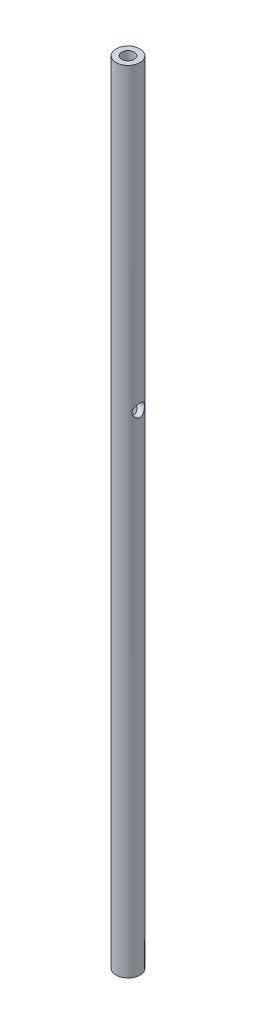
SolidWorks part; units mm, degrees
material "1060 Alloy"
ref_plane "Спереди" through (0, 0, 0) normal (0, 0, 1) x (1, 0, 0)
ref_plane "Сверху" through (0, 0, 0) normal (0, 1, 0) x (1, 0, 0)
ref_plane "Справа" through (0, 0, 0) normal (1, 0, 0) x (0, 0, -1)
sketch "Эскиз1" plane through (0, 0, 0) normal (0, 0, 1) x (1, 0, 0)
  line L0 (0, 0) -> (0, -630)
  dimension "D1" = 630
sketch "Эскиз2" plane through (0, 0, 0) normal (0, 1, 0) x (1, 0, 0)
  circle A0 centre (0, 0) radius 9.5
  circle A1 centre (0, 0) radius 5
  dimension "D1" = 19
  dimension "D2" = 10
sweep "По траектории1" add profiles "Эскиз2" path "Эскиз1"
sketch "Эскиз3" plane through (0, 0, 0) normal (1, 0, 0) x (0, 0, -1)
  line L0 (0, 0) -> (0, -343.1833) construction
  circle A0 centre (0, -240) radius 5
  dimension "D1" = 10
  dimension "D10" = 240
extrude "Вырез-Вытянуть1" cut sketch "Эскиз3" against normal through all and the other way through all
